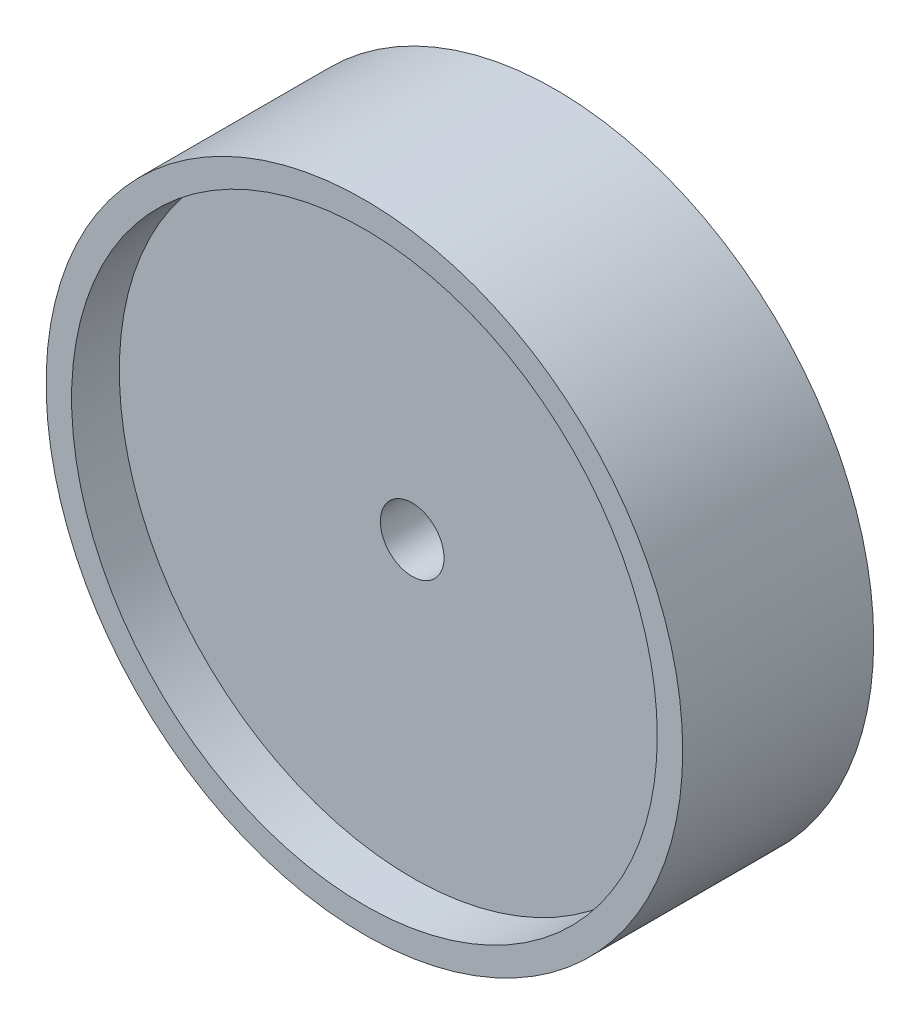
SolidWorks part; units mm, degrees
ref_plane "Front Plane" through (0, 0, 0) normal (0, 0, 1) x (1, 0, 0)
ref_plane "Top Plane" through (0, 0, 0) normal (0, 1, 0) x (1, 0, 0)
ref_plane "Right Plane" through (0, 0, 0) normal (1, 0, 0) x (0, 0, -1)
sketch "Sketch1" plane through (0, 0, 0) normal (0, 0, 1) x (1, 0, 0)
  circle A0 centre (0, 0) radius 230
  dimension "D1" = 460
extrude "Boss-Extrude1" add sketch "Sketch1" along normal blind 75
sketch "Sketch2" plane through (0, 0, 75) normal (0, 0, 1) x (1, 0, 0)
  circle A0 centre (0, 0) radius 230
  circle A1 centre (0, 0) radius 250
  dimension "D1" = 20
extrude "Boss-Extrude2" add sketch "Sketch2" along normal blind 37.5 and the other way blind 112.5 separate body
sketch "Sketch3" plane through (0, 0, 75) normal (0, 0, 1) x (1, 0, 0)
  circle A0 centre (0, 0) radius 25
  dimension "D1" = 50
extrude "Cut-Extrude1" cut sketch "Sketch3" against normal through all
